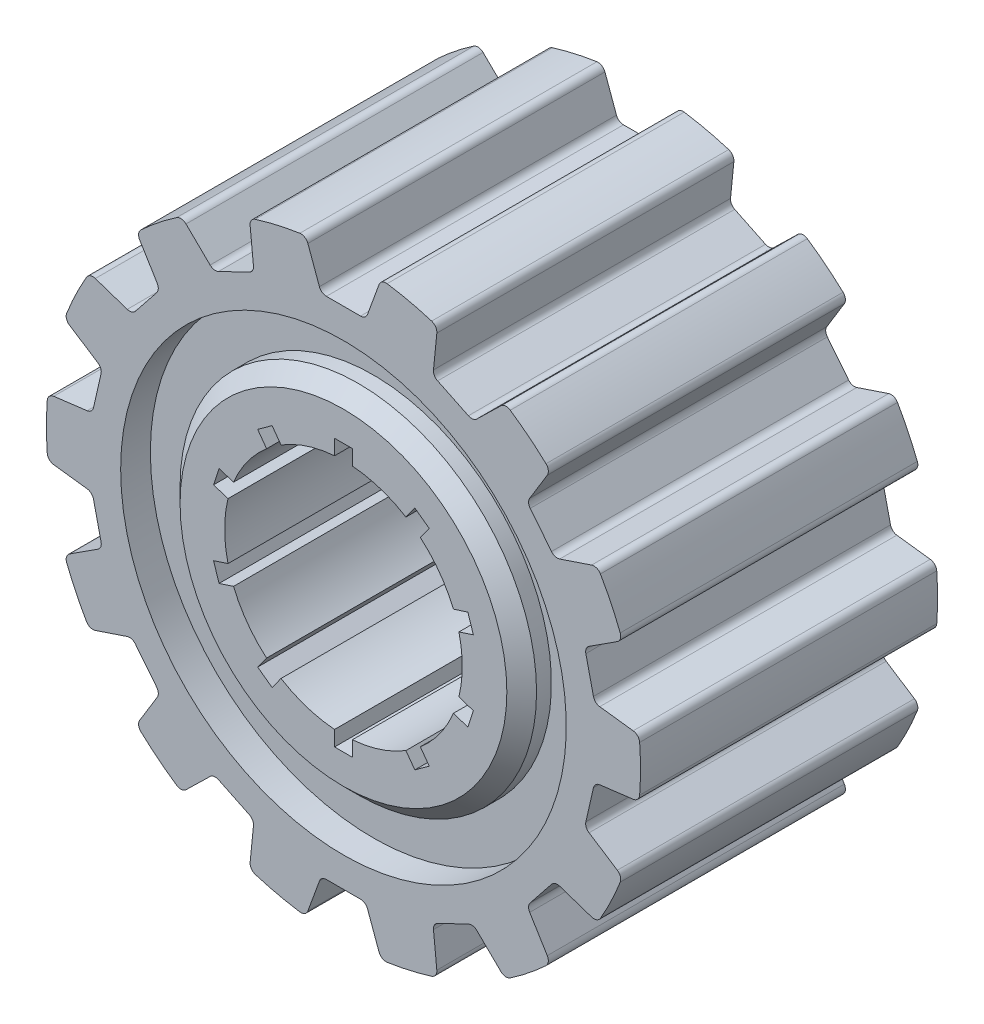
SolidWorks part; units mm, degrees
ref_plane "Front" through (0, 0, 0) normal (0, 0, 1) x (1, 0, 0)
ref_plane "Top" through (0, 0, 0) normal (0, 1, 0) x (1, 0, 0)
ref_plane "Right" through (0, 0, 0) normal (1, 0, 0) x (0, 0, -1)
sketch "Sketch1" plane through (0, 0, 0) normal (0, 0, 1) x (1, 0, 0)
  line L0 (0, 0) -> (0, 13.6818) construction
  line L1 (2.8877, 3.4642) -> (2.5872, 3.0506)
  line L2 (-0.3, 4.5) -> (0.3, 4.5)
  line L3 (-0.3, 4.5) -> (-0.3, 3.9887)
  line L5 (0.3, 4.5) -> (0.3, 3.9887)
  line L6 (2.4023, 3.8169) -> (2.8877, 3.4642)
  line L7 (2.4023, 3.8169) -> (2.1018, 3.4033)
  line L8 (4.3725, 1.1053) -> (3.8862, 0.9473)
  line L9 (4.187, 1.6759) -> (4.3725, 1.1053)
  line L10 (4.187, 1.6759) -> (3.7008, 1.5179)
  line L11 (4.187, -1.6759) -> (3.7008, -1.5179)
  line L12 (4.3725, -1.1053) -> (4.187, -1.6759)
  line L13 (4.3725, -1.1053) -> (3.8862, -0.9473)
  line L14 (2.4023, -3.8169) -> (2.1018, -3.4033)
  line L15 (2.8877, -3.4642) -> (2.4023, -3.8169)
  line L16 (2.8877, -3.4642) -> (2.5872, -3.0506)
  line L17 (-0.3, -4.5) -> (-0.3, -3.9887)
  line L18 (0.3, -4.5) -> (-0.3, -4.5)
  line L19 (0.3, -4.5) -> (0.3, -3.9887)
  line L20 (-2.8877, -3.4642) -> (-2.5872, -3.0506)
  line L21 (-2.4023, -3.8169) -> (-2.8877, -3.4642)
  line L22 (-2.4023, -3.8169) -> (-2.1018, -3.4033)
  line L23 (-4.3725, -1.1053) -> (-3.8862, -0.9473)
  line L24 (-4.187, -1.6759) -> (-4.3725, -1.1053)
  line L25 (-4.187, -1.6759) -> (-3.7008, -1.5179)
  line L26 (-4.187, 1.6759) -> (-3.7008, 1.5179)
  line L27 (-4.3725, 1.1053) -> (-4.187, 1.6759)
  line L28 (-4.3725, 1.1053) -> (-3.8862, 0.9473)
  line L29 (-2.4023, 3.8169) -> (-2.1018, 3.4033)
  line L30 (-2.8877, 3.4642) -> (-2.4023, 3.8169)
  line L31 (-2.8877, 3.4642) -> (-2.5872, 3.0506)
  arc A0 (-0.3, 3.9887) -> (-2.1018, 3.4033) centre (0, 0) ccw
  circle A1 centre (0, 0) radius 10
  arc A2 (-2.5872, 3.0506) -> (-3.7008, 1.5179) centre (0, 0) ccw
  arc A3 (-3.8862, 0.9473) -> (-3.8862, -0.9473) centre (0, 0) ccw
  arc A4 (-3.7008, -1.5179) -> (-2.5872, -3.0506) centre (0, 0) ccw
  arc A5 (-2.1018, -3.4033) -> (-0.3, -3.9887) centre (0, 0) ccw
  arc A6 (0.3, -3.9887) -> (2.1018, -3.4033) centre (0, 0) ccw
  arc A7 (2.5872, -3.0506) -> (3.7008, -1.5179) centre (0, 0) ccw
  arc A8 (3.8862, -0.9473) -> (3.8862, 0.9473) centre (0, 0) ccw
  arc A9 (3.7008, 1.5179) -> (2.5872, 3.0506) centre (0, 0) ccw
  arc A10 (2.1018, 3.4033) -> (0.3, 3.9887) centre (0, 0) ccw
  point P47 (0, 0)
  dimension "D1" = 20
  dimension "D2" = 8
  dimension "D3" = 0.6
  dimension "D4" = 4.5
  dimension "D5" = 10
extrude "Boss-Extrude1" add sketch "Sketch1" along normal blind 10
sketch "Sketch2" plane through (0, 0, 10) normal (0, 0, 1) x (1, 0, 0)
  line L0 (0, 0) -> (0, 13.4659) construction
  line L1 (-0.75, 8.5) -> (0.75, 8.5)
  line L2 (0.75, 8.5) -> (1.2666, 9.9195)
  line L3 (-0.75, 8.5) -> (-1.2666, 9.9195)
  circle A0 centre (0, 0) radius 10 construction
  dimension "D1" = 1.5
  dimension "D2" = 20
  dimension "D3" = 20
  dimension "D4" = 8.5
extrude "Cut-Extrude2" cut sketch "Sketch2" against normal blind 10 and the other way through all flip side to cut
pattern_circular "CirPattern1" count 14 over 360 about axis through (0, 0, 10) along (0, 0, -1) of "Cut-Extrude2"
ref_plane "Plane1" through (0, 0, 5) normal (0, 0, -1) x (-1, 0, 0)
sketch "Sketch5" plane through (0, 0, 5) normal (0, 0, -1) x (-1, 0, 0)
  line L0 (0, 0) -> (0, 14.9306) construction
  circle A0 centre (0, 0) radius 7.5
  circle A1 centre (0, 0) radius 6
  dimension "D1" = 15
  dimension "D2" = 12
extrude "Cut-Extrude8" cut sketch "Sketch5" along normal through all from offset 4
chamfer "Chamfer2" distance 0.5 angle 45 1 edges at (-6, 0, 0)
mirror "Mirror4" about plane through (0, 0, 5) normal (0, 0, -1) of "Cut-Extrude8"
chamfer "Chamfer3" distance 0.5 angle 45 1 edges at (-6, 0, 10)
fillet "Fillet5" radius 0.25 56 edges at (-4.3637, 7.3328, 5) (-3.0123, 7.9836, 5) (-1.2666, 9.9195, 5) (-0.75, 8.5, 5) (0.75, 8.5, 5) (1.2666, 9.9195, 5) (3.1627, 9.4867, 5) (3.0123, 7.9836, 5) (4.3637, 7.3328, 5) (5.4451, 8.3875, 5) (6.9656, 7.175, 5) (6.178, 5.886, 5) (7.1132, 4.7133, 5) (8.5451, 5.1944, 5) (9.3889, 3.4422, 5) (8.12, 2.6226, 5) (8.4538, 1.1602, 5) (9.9526, 0.9724, 5) (9.9526, -0.9724, 5) (8.4538, -1.1602, 5) (8.12, -2.6226, 5) (9.3889, -3.4422, 5) (8.5451, -5.1944, 5) (7.1132, -4.7133, 5) (6.178, -5.886, 5) (6.9656, -7.175, 5) (5.4451, -8.3875, 5) (4.3637, -7.3328, 5) (3.0123, -7.9836, 5) (3.1627, -9.4867, 5) (1.2666, -9.9195, 5) (0.75, -8.5, 5) (-0.75, -8.5, 5) (-1.2666, -9.9195, 5) (-3.1627, -9.4867, 5) (-3.0123, -7.9836, 5) (-4.3637, -7.3328, 5) (-5.4451, -8.3875, 5) (-6.9656, -7.175, 5) (-6.178, -5.886, 5) (-7.1132, -4.7133, 5) (-8.5451, -5.1944, 5) (-9.3889, -3.4422, 5) (-8.12, -2.6226, 5) (-8.4538, -1.1602, 5) (-9.9526, -0.9724, 5) (-9.9526, 0.9724, 5) (-8.4538, 1.1602, 5) (-8.12, 2.6226, 5) (-9.3889, 3.4422, 5) (-8.5451, 5.1944, 5) (-7.1132, 4.7133, 5) (-6.178, 5.886, 5) (-6.9656, 7.175, 5) (-5.4451, 8.3875, 5) (-3.1627, 9.4867, 5)
